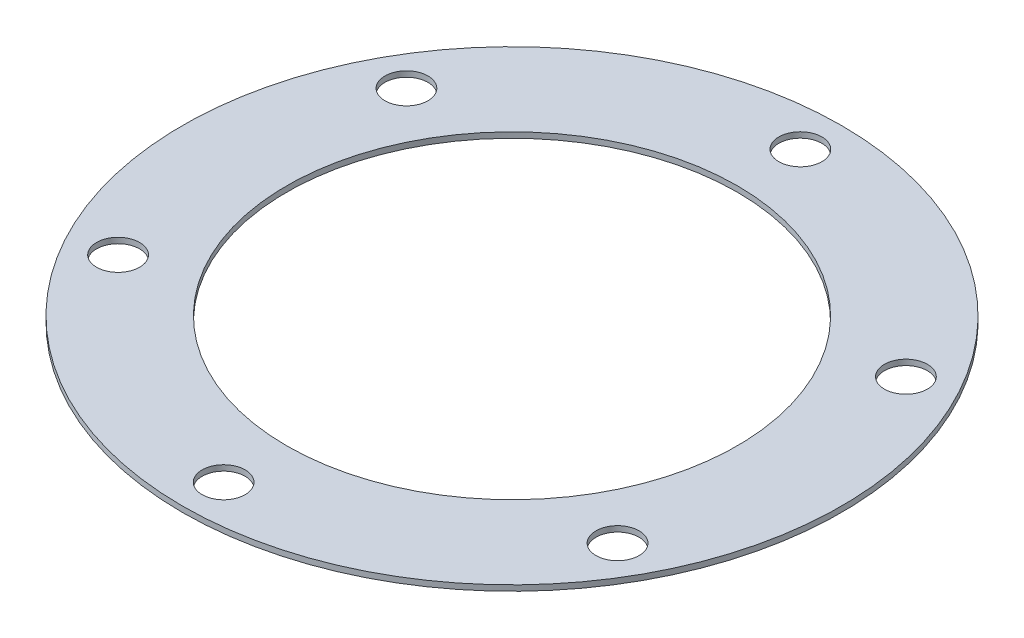
SolidWorks part; units mm, degrees
ref_plane "Front Plane" through (0, 0, 0) normal (0, 0, 1) x (1, 0, 0)
ref_plane "Top Plane" through (0, 0, 0) normal (0, 1, 0) x (1, 0, 0)
ref_plane "Right Plane" through (0, 0, 0) normal (1, 0, 0) x (0, 0, -1)
sketch "Sketch1" plane through (0, 0, 0) normal (0, 1, 0) x (1, 0, 0)
  circle A0 centre (0, 0) radius 50.8
  circle A1 centre (0, 0) radius 34.7272
  circle A2 centre (0, 44.45) radius 3.3147
  circle A3 centre (38.4948, 22.225) radius 3.3147
  circle A4 centre (38.4948, -22.225) radius 3.3147
  circle A5 centre (0, -44.45) radius 3.3147
  circle A6 centre (-38.4948, -22.225) radius 3.3147
  circle A7 centre (-38.4948, 22.225) radius 3.3147
  point P19 (0, 0)
  dimension "D1" = 69.4544
  dimension "D2" = 101.6
  dimension "D3" = 6.6294
  dimension "D4" = 44.45
  dimension "D5" = 6
extrude "Boss-Extrude1" add sketch "Sketch1" along normal blind 0.8636 contours A0 A7 A6 A5 A4 A3 A2 A1
